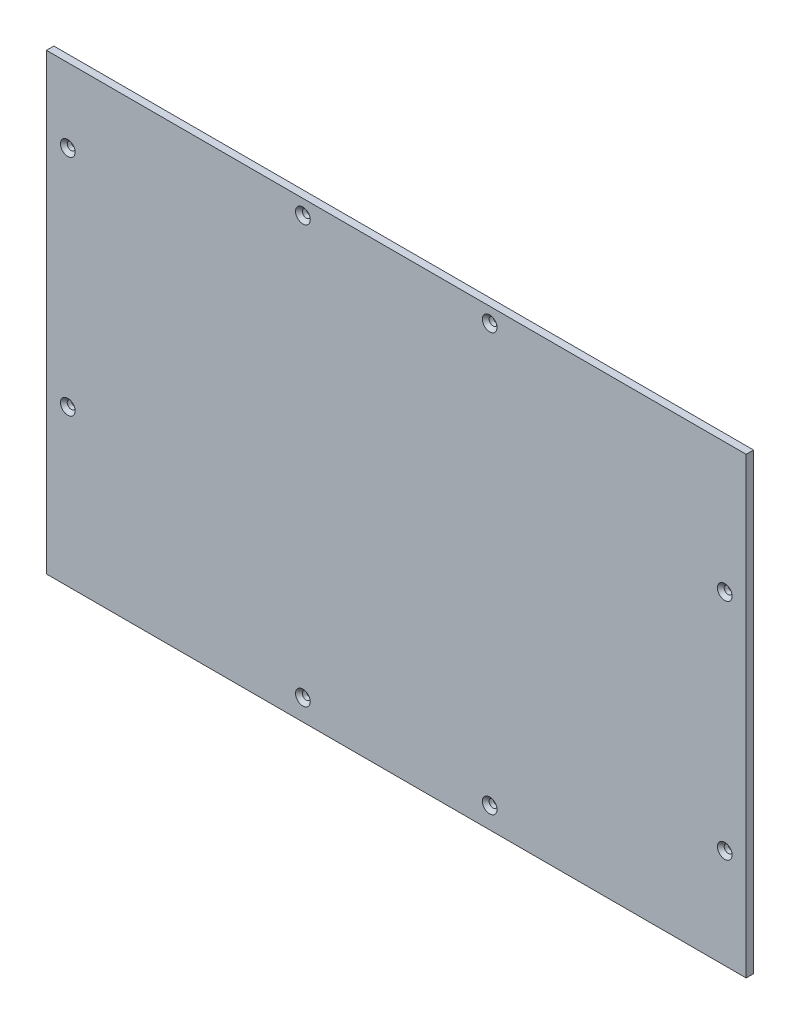
SolidWorks part; units mm, degrees
material "ABS"
ref_plane "X-Y Datum" through (0, 0, 0) normal (0, 0, 1) x (1, 0, 0)
ref_plane "X-Z Datum" through (0, 0, 0) normal (0, 1, 0) x (1, 0, 0)
ref_plane "Y-Z Datum" through (0, 0, 0) normal (1, 0, 0) x (0, 0, -1)
sketch "Sketch1" plane through (0, 0, 0) normal (0, 0, 1) x (1, 0, 0)
  line L0 (-149.85, 97.125) -> (-149.85, -97.125)
  line L1 (-149.85, 97.125) -> (149.85, 97.125)
  line L2 (-149.85, 97.125) -> (-149.85, -97.125)
  line L3 (-149.85, -97.125) -> (149.85, -97.125)
  line L4 (149.85, 97.125) -> (149.85, -97.125)
  line L5 (-149.85, 97.125) -> (149.85, -97.125) construction
  line L6 (-149.85, -97.125) -> (149.85, 97.125) construction
  line L7 (-149.85, -97.125) -> (149.85, -97.125)
  line L8 (149.85, 97.125) -> (149.85, -97.125)
  line L9 (-149.85, 97.125) -> (149.85, 97.125)
  circle A0 centre (-139.075, -86.35) radius 10.775
  circle A1 centre (-115.075, -86.35) radius 10.775 construction
  circle A2 centre (-127.075, -63.35) radius 10.775
  point P0 (0, 0)
  dimension "D1" = 21.55
  dimension "D2" = 24
  dimension "D3" = 23
  dimension "D4" = 12
  dimension "D5" = 194.25
  dimension "D6" = 299.7
  dimension "D7" = 0
extrude "Boss-Extrude1" add sketch "Sketch1" along normal blind 3.175 contours A0 L3 L4 L1 L2 A2 | A2 | A0 | A0 L2 L3 | L9 L0 L7 L8 L1 L4 L3 L2
sketch "Sketch2" plane through (0, 0, 3.175) normal (0, 0, 1) x (1, 0, 0)
  point P0 (140.6875, -54.525)
  point P1 (140.6875, 41.475)
  point P3 (-40, 90.775)
  point P5 (40, 90.775)
  point P7 (-140.6875, 65.475)
  point P9 (-140.6875, -30.525)
  point P11 (40, -88.0307)
  point P13 (-40, -88.0307)
hole_wizard "CSK for M3 Flat Head Machine Screw1" positions "Sketch3" profile "Sketch4" countersink size "M3" standard "ANSI Metric" end condition through all
sketch "Sketch3" plane through (0, 0, 3.175) normal (0, 0, 1) x (1, 0, 0)
  point P0 (-40, 90.775)
  point P3 (140.6875, 41.475)
  point P6 (140.6875, -54.525)
  point P9 (40, -88.0307)
  point P12 (-40, -88.0307)
  point P15 (-140.6875, -30.525)
  point P18 (-140.6875, 65.475)
  point P21 (40, 90.775)
sketch "Sketch4" plane through (-40, 90.775, 3.175) normal (1, 0, 0) x (0, -1, 0)
  line L0 (0, 0) -> (0, 3.175)
  line L1 (0, 3.175) -> (1.7, 3.175)
  line L2 (1.7, 3.175) -> (1.7, 1.45)
  line L3 (1.7, 1.45) -> (3.15, 0)
  line L5 (3.15, 0) -> (0, 0)
  line L6 (-1.7, 1.45) -> (-3.15, 0) construction
  line L11 (0, -6.35) -> (0, 107.95) construction
  dimension "Thru Hole Dia." = 3.4
  dimension "Thru Hole Depth" = 3.175
  dimension "Near C'Sink Dia." = 6.3
  dimension "Near C'Sink Angle" = 90
